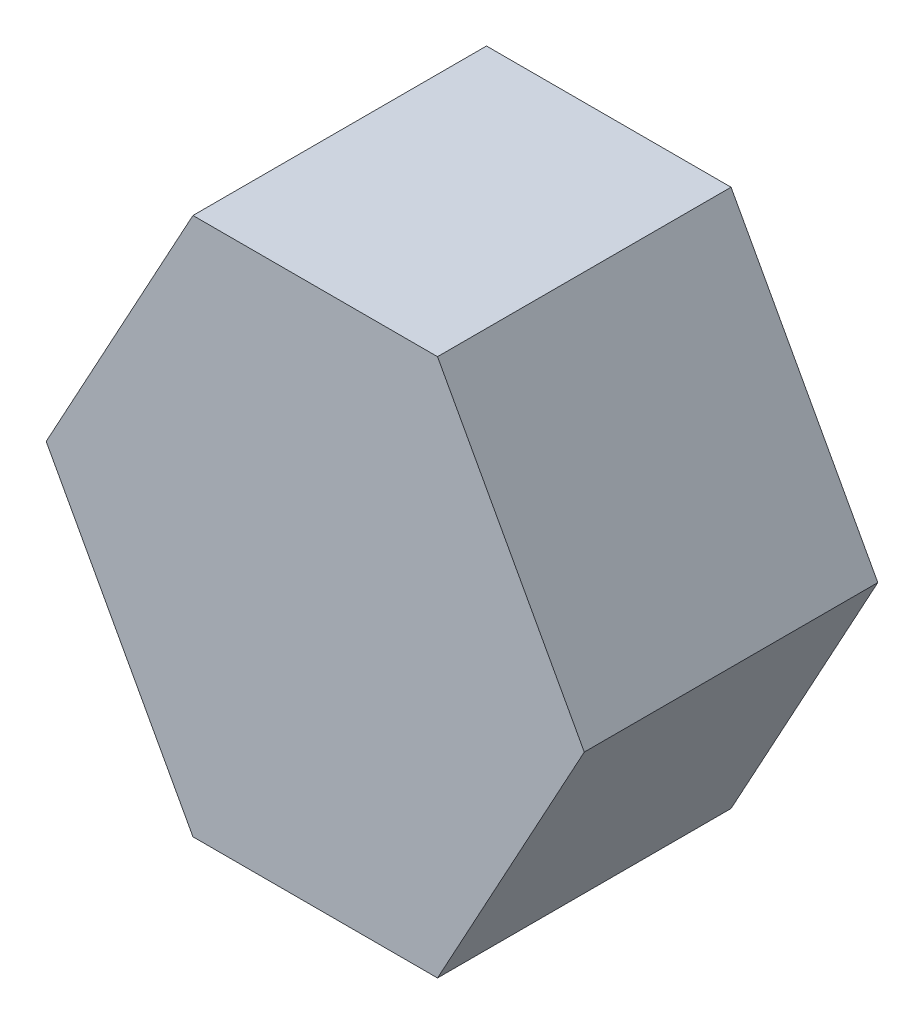
SolidWorks part; units mm, degrees
ref_plane "Front Plane" through (0, 0, 0) normal (0, 0, 1) x (1, 0, 0)
ref_plane "Top Plane" through (0, 0, 0) normal (0, 1, 0) x (1, 0, 0)
ref_plane "Right Plane" through (0, 0, 0) normal (1, 0, 0) x (0, 0, -1)
sketch "Sketch1" plane through (0, 0, 0) normal (0, 0, 1) x (1, 0, 0)
  line L1 (-6.35, 6.35) -> (6.35, 6.35)
  line L2 (-6.35, 6.35) -> (-6.35, -6.35)
  line L3 (-6.35, -6.35) -> (6.35, -6.35)
  line L4 (6.35, 6.35) -> (6.35, -6.35)
  dimension "D1" = 6.35
  dimension "D2" = 6.35
  dimension "D3" = 12.7
  dimension "D4" = 6.35
extrude "Boss-Extrude1" add sketch "Sketch1" along normal blind 6.928
hole_wizard "Tap Drill for M3x0.5 Tap3" positions "Sketch7" profile "Sketch6" hole size "M3x0.5" standard "BSI"
sketch "Sketch7" plane through (0, 0, 0) normal (0, 0, 1) x (1, 0, 0)
  point P0 (0, 0)
sketch "Sketch6" plane through (0, 0, 0) normal (1, 0, 0) x (0, 1, 0)
  line L0 (0, 0) -> (0, 4.7511)
  line L1 (0, 4.7511) -> (1.25, 4)
  line L2 (1.25, 4) -> (1.25, 0)
  line L5 (1.25, 0) -> (0, 0)
  line L10 (0, 4.7511) -> (-1.25, 4) construction
  line L11 (0, -6.35) -> (0, 107.95) construction
  dimension "Hole Dia." = 2.5
  dimension "Hole Depth" = 4
  dimension "Drill Angle" = 118
sketch "Sketch8" plane through (0, 0, 0) normal (0, 0, 1) x (1, 0, 0)
  line L0 (2.886, 6.35) -> (6.35, 0)
  line L1 (6.35, 6.35) -> (-6.35, 6.35) construction
  line L2 (6.35, -6.35) -> (6.35, 6.35) construction
  dimension "D1" = 3.464
extrude "Cut-Extrude1" cut sketch "Sketch8" against normal through all and the other way through all
mirror "Mirror1" about plane through (0, 0, 0) normal (0, 1, 0) of "Cut-Extrude1"
mirror "Mirror2" about plane through (0, 0, 0) normal (1, 0, 0) of "Mirror1", "Cut-Extrude1"
